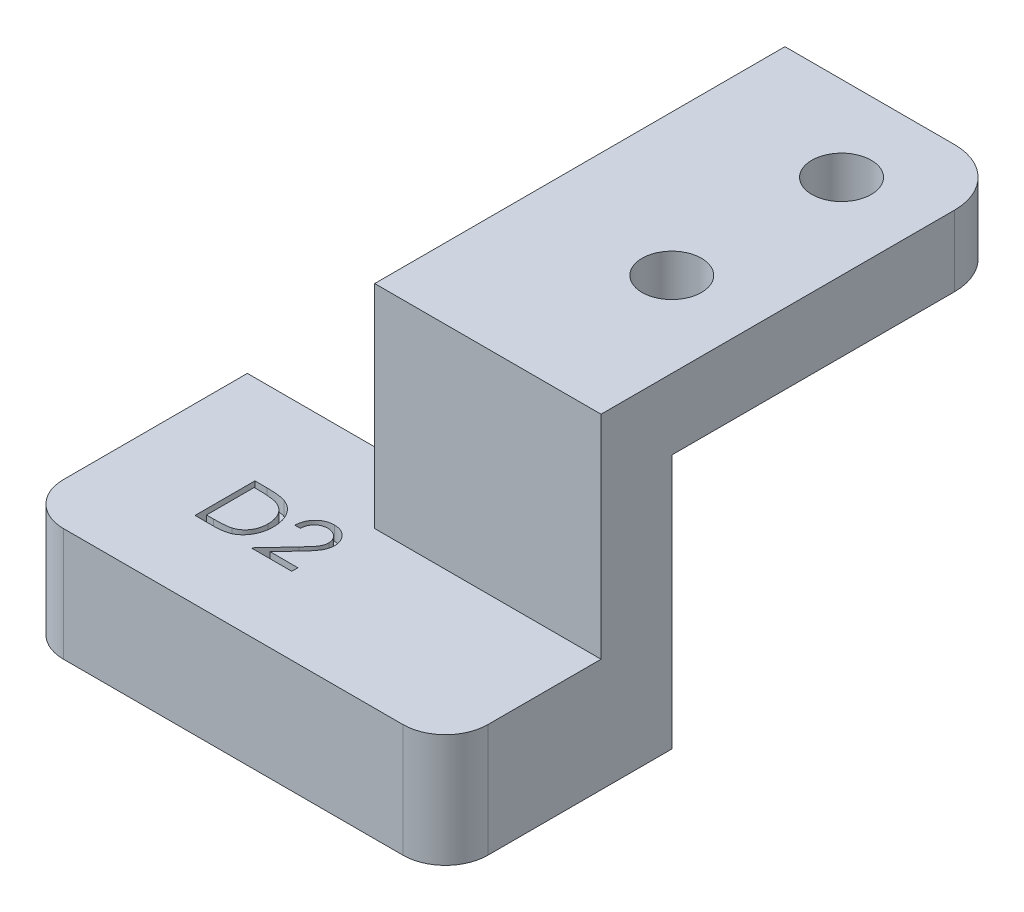
SolidWorks part; units mm, degrees
ref_plane "Front Plane" through (0, 0, 0) normal (0, 0, 1) x (1, 0, 0)
ref_plane "Top Plane" through (0, 0, 0) normal (0, 1, 0) x (1, 0, 0)
ref_plane "Right Plane" through (0, 0, 0) normal (1, 0, 0) x (0, 0, -1)
sketch "Sketch1" plane through (0, 0, 0) normal (0, 1, 0) x (1, 0, 0)
  line L1 (-7.5, -4) -> (7.5, -4)
  line L2 (-7.5, -4) -> (-7.5, 4)
  line L3 (-7.5, 4) -> (7.5, 4)
  line L4 (7.5, -4) -> (7.5, 4)
  line L5 (-7.5, -4) -> (7.5, 4) construction
  line L6 (-7.5, 4) -> (7.5, -4) construction
  point P0 (0, 0)
  dimension "D1" = 8
  dimension "D2" = 15
extrude "Boss-Extrude1" add sketch "Sketch1" along normal blind 4
fillet "Fillet1" radius 1.5 2 edges at (-7.5, 2, 4) (7.5, 2, 4)
sketch "Sketch10" plane through (0, 4, 0) normal (0, 1, 0) x (1, 0, 0)
  line L0 (7.5, -2.5) -> (7.5, 4) construction
  line L1 (-7.5, 4) -> (-0.5, 4)
  line L2 (-7.5, 4) -> (-7.5, 0)
  line L3 (-7.5, 0) -> (-0.5, 0)
  line L4 (-0.5, 4) -> (-0.5, 0)
  dimension "D1" = 4
  dimension "D2" = 8
extrude "Cut-Extrude2" cut sketch "Sketch10" against normal blind 7.5
sketch "Sketch11" plane through (0, 4, 0) normal (0, 1, 0) x (1, 0, 0)
  line L0 (7.5, -2.5) -> (7.5, 4) construction
  line L1 (-0.5, 4) -> (7.5, 4)
  line L2 (-0.5, 4) -> (-0.5, 1.5)
  line L3 (-0.5, 1.5) -> (7.5, 1.5)
  line L4 (7.5, 4) -> (7.5, 1.5)
  dimension "D1" = 2.5
extrude "Boss-Extrude4" add sketch "Sketch11" along normal blind 7.5
sketch "Sketch12" plane through (0, 0, -4) normal (0, 0, -1) x (-1, 0, 0)
  line L0 (0.5, 0) -> (0.5, 11.5) construction
  line L1 (-7.5, 11.5) -> (0.5, 11.5)
  line L2 (-7.5, 11.5) -> (-7.5, 9)
  line L3 (-7.5, 9) -> (0.5, 9)
  line L4 (0.5, 11.5) -> (0.5, 9)
  dimension "D1" = 2.5
extrude "Boss-Extrude5" add sketch "Sketch12" along normal blind 12
fillet "Fillet2" radius 2 1 edges at (7.5, 10.25, -16)
sketch "Sketch13" plane through (0, 11.5, 0) normal (0, 1, 0) x (1, 0, 0)
  line L0 (-0.5, 16) -> (5.5, 16) construction
  line L1 (-0.5, 16) -> (-0.5, 1.5) construction
  circle A0 centre (4.5, 13) radius 1.05
  circle A1 centre (4.5, 7) radius 1.0492
  dimension "D1" = 2.1
  dimension "D2" = 2.0984
  dimension "D3" = 3
  dimension "D4" = 6
  dimension "D5" = 5
  dimension "D6" = 5
extrude "Cut-Extrude3" cut sketch "Sketch13" against normal blind 12
sketch "Sketch14" plane through (0, 9, 0) normal (0, -1, 0) x (-1, 0, 0)
  line L0 (0.5, 16) -> (0.5, 4) construction
  line L1 (-7.5, 4) -> (0.5, 4)
  line L2 (-7.5, 4) -> (-7.5, 5.9362)
  line L3 (-7.5, 5.9362) -> (0.5, 5.9362)
  line L4 (0.5, 4) -> (0.5, 5.9362)
extrude "Boss-Extrude6" add sketch "Sketch14" along normal blind 7.5
ref_plane "Plane1" through (-0.5, 0, -4) normal (0, 0, 1) x (1, 0, 0)
sketch "Sketch16" plane through (0, 0, 0) normal (0, 0, -1) x (-1, 0, 0)
  line L1 (7.5, 4) -> (0.5, 4)
  line L2 (7.5, 4) -> (7.5, 0)
  line L3 (7.5, 0) -> (0.5, 0)
  line L4 (0.5, 4) -> (0.5, 0)
extrude "Boss-Extrude7" add sketch "Sketch16" along normal blind 4
sketch "Sketch17" plane through (7.5, 0, 0) normal (1, 0, 0) x (0, 0, -1)
  line L0 (4, 1.1) -> (4, -1.1) construction
  line L1 (5.9362, 1.5) -> (4, 1.5)
  line L2 (5.9362, 1.5) -> (5.9362, 9.0002)
  line L3 (5.9362, 9.0002) -> (4, 9.0002)
  line L4 (4, 1.5) -> (4, 9.0002)
extrude "Cut-Extrude4" cut sketch "Sketch17" against normal blind 8
sketch "Sketch19" plane through (0, 4, 0) normal (0, 1, 0) x (1, 0, 0)
  text T0 "D2" font "Century Gothic" height in points 8
extrude "Cut-Extrude5" cut sketch "Sketch19" against normal blind 0.5
